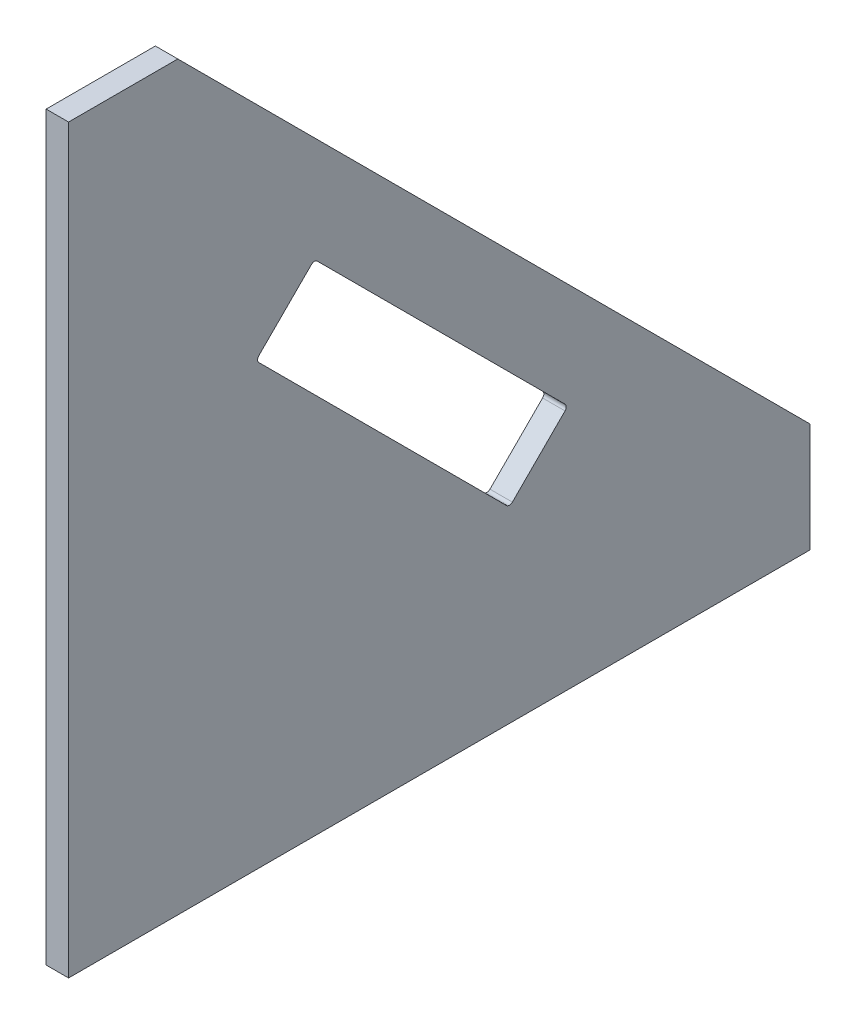
SolidWorks part; units mm, degrees
material "Pine"
ref_plane "Front Plane" through (0, 0, 0) normal (0, 0, 1) x (1, 0, 0)
ref_plane "Top Plane" through (0, 0, 0) normal (0, 1, 0) x (1, 0, 0)
ref_plane "Right Plane" through (0, 0, 0) normal (1, 0, 0) x (0, 0, -1)
sketch "Sketch1" plane through (0, 0, 0) normal (1, 0, 0) x (0, 0, -1)
  line L0 (0, 0) -> (0, 603.25)
  line L1 (0, 603.25) -> (88.9, 603.25)
  line L2 (88.9, 603.25) -> (603.25, 88.9)
  line L3 (603.25, 88.9) -> (603.25, 0)
  line L4 (603.25, 0) -> (0, 0)
  dimension "D1" = 603.25
  dimension "D2" = 88.9
extrude "Boss-Extrude1" add sketch "Sketch1" along normal blind 18.2562
sketch "Sketch7" plane through (18.2562, 0, 0) normal (1, 0, 0) x (0, 0, -1)
  line L0 (0, 0) -> (346.075, 346.075) construction
  line L1 (603.25, 88.9) -> (88.9, 603.25) construction
  line L7 (200.025, 406.4) -> (406.4, 200.025)
  line L8 (358.775, 152.4) -> (406.4, 200.025)
  line L9 (152.4, 358.775) -> (358.775, 152.4)
  line L10 (0, 0) -> (603.25, 0) construction
  line L11 (0, 603.25) -> (0, 0) construction
  line L12 (200.025, 406.4) -> (152.4, 358.775)
  point P13 (200.025, 406.4)
  point P14 (152.4, 358.775)
  dimension "D1" = 200.025
  dimension "D2" = 152.4
  dimension "D3" = 358.775
  dimension "D4" = 406.4
  dimension "D5" = 358.775
  dimension "D6" = 406.4
  dimension "D7" = 152.4
  dimension "D8" = 200.025
extrude "Cut-Extrude2" cut sketch "Sketch7" against normal through all
fillet "Fillet2" radius 3.3782 4 edges at (9.1281, 406.4, -200.025) (9.1281, 152.4, -358.775) (9.1281, 358.775, -152.4) (9.1281, 200.025, -406.4)
